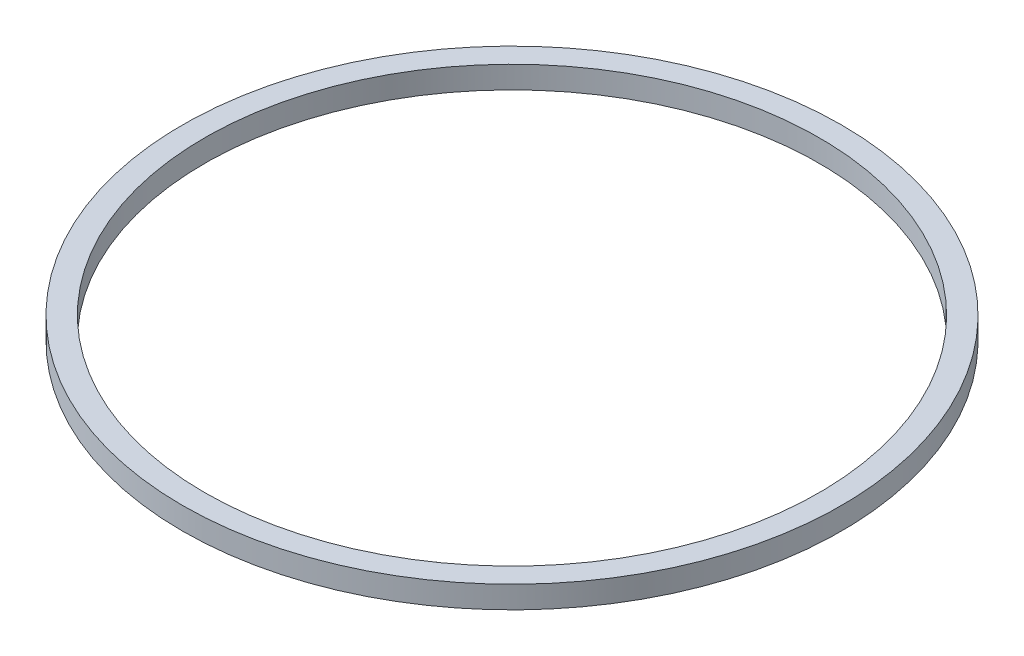
SolidWorks part; units mm, degrees
ref_plane "Front Plane" through (0, 0, 0) normal (0, 0, 1) x (1, 0, 0)
ref_plane "Top Plane" through (0, 0, 0) normal (0, 1, 0) x (1, 0, 0)
ref_plane "Right Plane" through (0, 0, 0) normal (1, 0, 0) x (0, 0, -1)
sketch "Sketch1" plane through (0, 0, 0) normal (0, 1, 0) x (1, 0, 0)
  circle A0 centre (0, 0) radius 41.5
  circle A1 centre (0, 0) radius 44.5
  dimension "D1" = 3
  dimension "D2" = 83
extrude "Boss-Extrude1" add sketch "Sketch1" along normal blind 3
